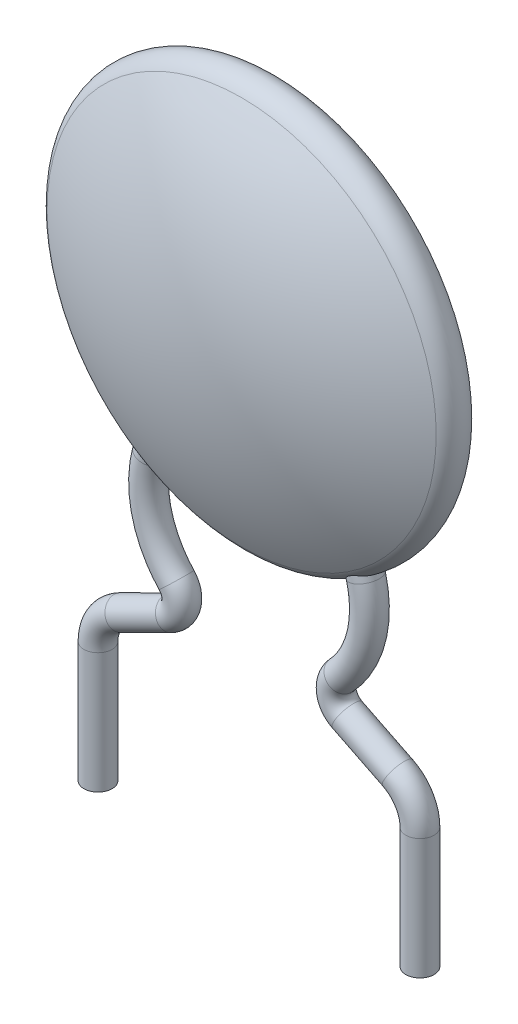
SolidWorks part; units mm, degrees
ref_plane "Спереди" through (0, 0, 0) normal (0, 0, 1) x (1, 0, 0)
ref_plane "Сверху" through (0, 0, 0) normal (0, 1, 0) x (1, 0, 0)
ref_plane "Справа" through (0, 0, 0) normal (1, 0, 0) x (0, 0, -1)
sketch "Эскиз1" plane through (0, 0, 0) normal (0, 1, 0) x (1, 0, 0)
  line L0 (-5.5, 0) -> (0, 0) construction
  line L1 (0, -0.7214) -> (0, 3.2789) construction
  line L2 (0, 1.75) -> (0, -1.75)
  arc A0 (0, -1.75) -> (-4.8346, -0.4307) centre (0, 7.7679) cw
  arc A1 (0, 1.75) -> (-4.8346, 0.4307) centre (0, -7.7679) ccw
  arc A4 (-4.8346, 0.4307) -> (-4.8346, -0.4307) centre (-4.5806, 0) ccw
  dimension "D2" = 3.5
  dimension "D3" = 0.5
  dimension "D1" = 5.5
revolve "Повернуть7" add sketch "Эскиз1" angle 360 about L1
sketch "Эскиз2" plane through (0, 0, 0) normal (0, 1, 0) x (1, 0, 0)
  circle A0 centre (2, 0) radius 0.35
  point P2 (0, 0)
  point P4 (0, 0)
  dimension "D2" = 0.7
  dimension "D1" = 2
sketch "Эскиз3" plane through (0, 0, 0) normal (0, 0, 1) x (1, 0, 0)
  line L0 (2, 0) -> (2, -1.8214)
  line L1 (2.35, 0) -> (1.65, 0) construction
  line L2 (2.0357, -2.0862) -> (2.6527, -4.3331)
  line L3 (2.1907, -7.5629) -> (3.4444, -8.1848)
  line L4 (4, -9.0806) -> (4, -12.0806)
  line L5 (0, 0) -> (0, -13.7113) construction
  circle A0 centre (0, 0) radius 5.0806 construction
  arc A1 (2.6527, -4.3331) -> (2.0494, -6.7862) centre (0.154, -5.0193) cw
  arc A2 (2.0494, -6.7862) -> (2.1907, -7.5629) centre (2.4095, -7.1219) ccw
  arc A3 (2, -1.8214) -> (2.0357, -2.0862) centre (3, -1.8214) ccw
  arc A4 (3.4444, -8.1848) -> (4, -9.0806) centre (3, -9.0806) cw
  point P0 (2, 0)
  point P21 (2.5122, -6.9642)
  point P22 (0, 0)
  point P23 (3.4349, -8.5788)
  point P24 (2.525, -7.1692)
  point P26 (3.5246, -8.7711)
  point P27 (2.4778, -7.0924)
  point P28 (2.1717, -7.2514)
  point P29 (0, 0)
  point P30 (2.8757, -4.1885)
  point P31 (2.3675, -6.856)
  point P32 (2.5022, -6.3159)
  point P33 (3, -4.0904)
  point P34 (2.2431, -6.6613)
  point P35 (2.797, -7.2453)
  point P36 (2.4723, -7.8797)
  point P37 (2.6404, -4.3331)
  point P38 (0, 0)
  point P39 (2.1555, -6.6652)
  point P40 (2.1907, -7.5629)
  dimension "D1" = 1
  dimension "D2" = 1
  dimension "D4" = 3
  dimension "D3" = 4
  dimension "D6" = 4
sweep "По траектории1" add profiles "Эскиз2" path "Эскиз3"
mirror "Зеркальное отражение1" about plane through (0, 0, 0) normal (1, 0, 0) of "По траектории1"
